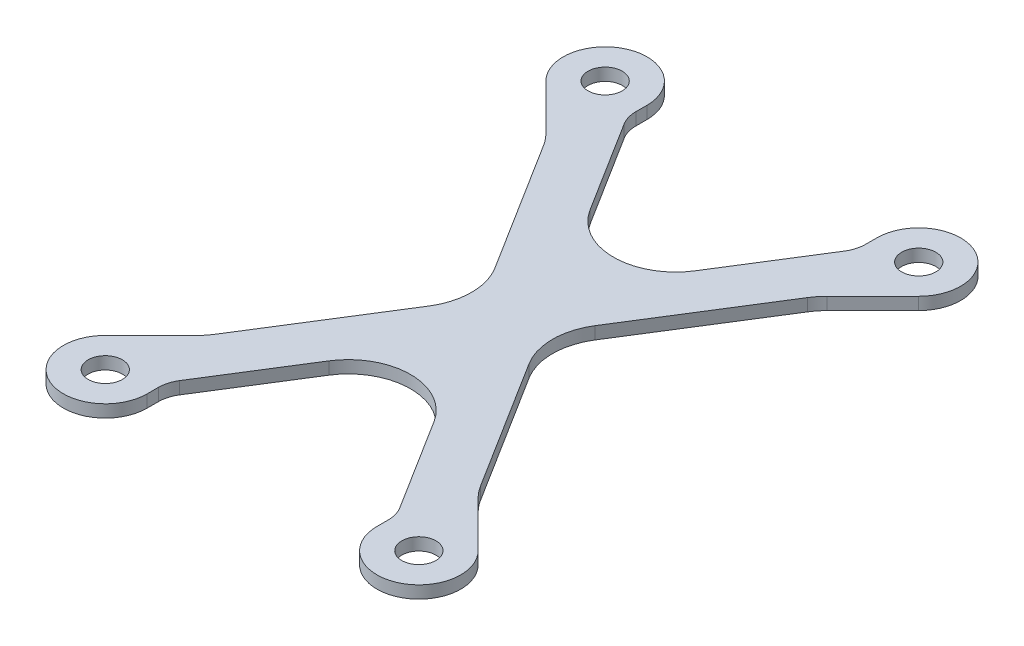
SolidWorks part; units mm, degrees
material "Hexcel AS4C (3000 Filaments)"
ref_plane "Front Plane" through (0, 0, 0) normal (0, 0, 1) x (1, 0, 0)
ref_plane "Top Plane" through (0, 0, 0) normal (0, 1, 0) x (1, 0, 0)
ref_plane "Right Plane" through (0, 0, 0) normal (1, 0, 0) x (0, 0, -1)
sketch "Sketch1" plane through (0, 0, 0) normal (0, 1, 0) x (1, 0, 0)
  line L7 (-21.2508, 26.348) -> (-8.0557, 5.3142)
  line L10 (-21.2945, -26.4177) -> (-8.0557, -5.3142)
  line L11 (-25.25, -40.25) -> (25.25, 40.25) construction
  line L12 (8.4711, 21.0305) -> (17.7356, 35.7986)
  line L13 (-17.7356, -35.7986) -> (-8.4711, -21.0305)
  line L14 (21.2508, 26.348) -> (8.0557, 5.3142)
  line L15 (25.25, -40.25) -> (-25.25, 40.25) construction
  line L16 (17.7356, -35.7986) -> (8.4711, -21.0305)
  line L17 (-8.4711, 21.0305) -> (-17.7356, 35.7986)
  line L19 (21.2508, -26.348) -> (8.0557, -5.3142)
  line L21 (-30.023, 35.477) -> (-22.6508, 28.1049)
  line L22 (30.023, 35.477) -> (22.6508, 28.1049)
  line L23 (-18.5, 40.25) -> (-18.5, 38.4557)
  line L24 (30.023, -35.477) -> (22.6508, -28.1049)
  line L25 (18.5, 40.25) -> (18.5, 38.4557)
  line L27 (18.5, -40.25) -> (18.5, -38.4557)
  line L30 (-30.3617, -35.8417) -> (-22.6945, -28.1745)
  line L32 (-18.5, -38.4557) -> (-18.5, -40.25)
  circle A1 centre (-25.25, 40.25) radius 2.75
  circle A3 centre (25.25, 40.25) radius 2.75
  circle A5 centre (25.25, -40.25) radius 2.75
  circle A7 centre (-25.25, -40.25) radius 2.75
  arc A8 (-28.6384, -38.1243) -> (-21.8616, -42.3757) centre (-25.25, -40.25) ccw
  arc A9 (28.6384, 38.1243) -> (21.8616, 42.3757) centre (25.25, 40.25) ccw
  arc A10 (21.8616, -42.3757) -> (28.6384, -38.1243) centre (25.25, -40.25) ccw
  arc A11 (-21.8616, 42.3757) -> (-28.6384, 38.1243) centre (-25.25, 40.25) ccw
  arc A17 (8.0557, 5.3142) -> (8.0557, -5.3142) centre (16.5268, 0) ccw
  arc A18 (-8.0557, 5.3142) -> (-8.0557, -5.3142) centre (-16.5268, 0) cw
  arc A19 (8.4711, -21.0305) -> (-8.4711, -21.0305) centre (0, -26.3447) ccw
  arc A20 (8.4711, 21.0305) -> (-8.4711, 21.0305) centre (0, 26.3447) cw
  circle A21 centre (-25.25, 40.25) radius 6.75
  circle A22 centre (25.25, 40.25) radius 6.75
  circle A23 centre (-25.25, -40.25) radius 6.75
  circle A24 centre (25.25, -40.25) radius 6.75
  arc A25 (21.2508, 26.348) -> (22.6508, 28.1049) centre (29.7219, 21.0338) cw
  arc A26 (-21.2508, 26.348) -> (-22.6508, 28.1049) centre (-29.7219, 21.0338) ccw
  arc A27 (17.7356, 35.7986) -> (18.5, 38.4557) centre (13.5, 38.4557) ccw
  arc A28 (-17.7356, 35.7986) -> (-18.5, 38.4557) centre (-13.5, 38.4557) cw
  arc A29 (17.7356, -35.7986) -> (18.5, -38.4557) centre (13.5, -38.4557) cw
  arc A30 (-17.7356, -35.7986) -> (-18.5, -38.4557) centre (-13.5, -38.4557) ccw
  arc A31 (21.2508, -26.348) -> (22.6508, -28.1049) centre (29.7219, -21.0338) ccw
  arc A32 (-21.2945, -26.4177) -> (-22.6945, -28.1745) centre (-29.7656, -21.1035) cw
  point P1 (0, 0)
  point P13 (0, 0)
  dimension "D1" = 10
  dimension "D2" = 4
  dimension "D3" = 10
  dimension "D4" = 5
  dimension "D5" = 5
  dimension "D6" = 10
extrude "Boss-Extrude1" add sketch "Sketch1" along normal blind 2
